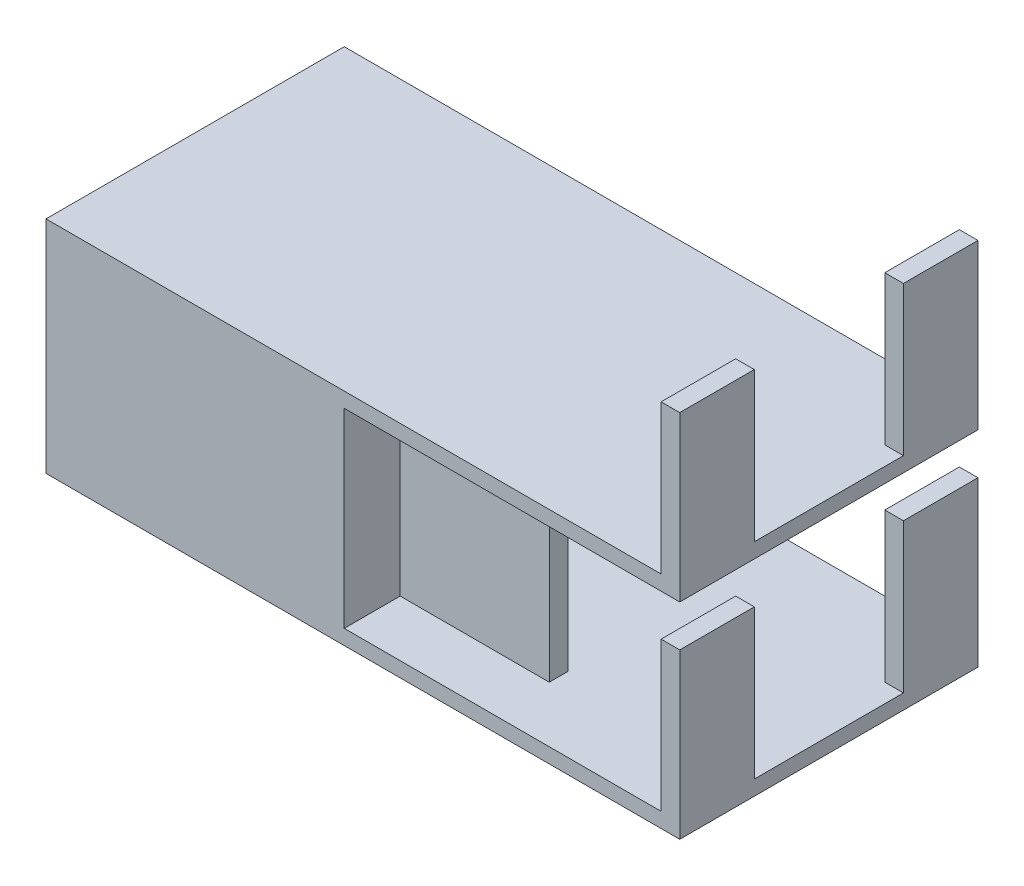
SolidWorks part; units mm, degrees
ref_plane "Front Plane" through (0, 0, 0) normal (0, 0, 1) x (1, 0, 0)
ref_plane "Top Plane" through (0, 0, 0) normal (0, 1, 0) x (1, 0, 0)
ref_plane "Right Plane" through (0, 0, 0) normal (1, 0, 0) x (0, 0, -1)
sketch "Sketch1" plane through (0, 0, 0) normal (0, 1, 0) x (1, 0, 0)
  line L1 (25.4, -25.4) -> (-25.4, -25.4)
  line L2 (25.4, -25.4) -> (25.4, 25.4)
  line L3 (25.4, 25.4) -> (-25.4, 25.4)
  line L4 (-25.4, -25.4) -> (-25.4, 25.4)
  line L5 (25.4, -25.4) -> (-25.4, 25.4) construction
  line L6 (25.4, 25.4) -> (-25.4, -25.4) construction
  point P0 (0, 0)
  dimension "D1" = 50.8
extrude "Boss-Extrude1" add sketch "Sketch1" along normal blind 2.54
sketch "Sketch2" plane through (0, 2.54, 0) normal (0, 1, 0) x (1, 0, 0)
  circle A0 centre (0, 0) radius 19.05
  dimension "D1" = 38.1
extrude "Cut-Extrude1" cut sketch "Sketch2" against normal through all
sketch "Sketch3" plane through (0, 2.54, 0) normal (0, 1, 0) x (1, 0, 0)
  line L1 (15.494, -15.494) -> (-15.494, -15.494) construction
  line L2 (15.494, -15.494) -> (15.494, 15.494) construction
  line L3 (15.494, 15.494) -> (-15.494, 15.494) construction
  line L4 (-15.494, -15.494) -> (-15.494, 15.494) construction
  line L5 (15.494, -15.494) -> (-15.494, 15.494) construction
  line L6 (15.494, 15.494) -> (-15.494, -15.494) construction
  circle A0 centre (-15.494, 15.494) radius 1.905
  circle A1 centre (15.494, 15.494) radius 1.905
  circle A2 centre (15.494, -15.494) radius 1.905
  circle A3 centre (-15.494, -15.494) radius 1.905
  point P0 (0, 0)
  dimension "D2" = 3.81
  dimension "D1" = 30.988
extrude "Cut-Extrude2" cut sketch "Sketch3" against normal through all
sketch "Sketch4" plane through (0, 2.54, 0) normal (0, 1, 0) x (1, 0, 0)
  line L0 (-25.4, -25.4) -> (25.4, -25.4) construction
  line L1 (-10.795, -25.4) -> (10.795, -25.4)
  line L2 (-10.795, -25.4) -> (-10.795, -15.6962)
  line L3 (-10.795, -15.6962) -> (10.795, -15.6962)
  line L4 (10.795, -25.4) -> (10.795, -15.6962)
  circle A0 centre (0, 0) radius 19.05 construction
  point P6 (0, -25.4)
  point P8 (0, 0)
  dimension "D1" = 21.59
extrude "Cut-Extrude3" cut sketch "Sketch4" against normal through all
sketch "Sketch5" plane through (0, 2.54, 0) normal (0, 1, 0) x (1, 0, 0)
  line L1 (-25.4, -25.4) -> (-22.225, -25.4)
  line L2 (-25.4, -25.4) -> (-25.4, -6.35)
  line L3 (-25.4, -6.35) -> (-22.225, -6.35)
  line L4 (-22.225, -25.4) -> (-22.225, -6.35)
  line L5 (25.4, -25.4) -> (22.225, -25.4)
  line L6 (25.4, -25.4) -> (25.4, -6.35)
  line L7 (25.4, -6.35) -> (22.225, -6.35)
  line L8 (22.225, -25.4) -> (22.225, -6.35)
  point P9 (0, 0)
  point P10 (0, 0)
  dimension "D1" = 3.175
  dimension "D2" = 19.05
extrude "Boss-Extrude2" add sketch "Sketch5" along normal blind 35.0058
sketch "Sketch6" plane through (0, 37.5458, 0) normal (0, 1, 0) x (1, 0, 0)
  line L0 (25.4, -25.4) -> (25.4, -6.35) construction
  line L1 (-25.4, -25.4) -> (25.4, -25.4)
  line L2 (-25.4, -25.4) -> (-25.4, 25.4)
  line L4 (25.4, -25.4) -> (25.4, 25.4)
  line L7 (25.4, 25.4) -> (-25.4, 25.4) construction
  line L8 (-25.4, 25.4) -> (25.4, 25.4)
extrude "Boss-Extrude3" add sketch "Sketch6" against normal blind 2.54
sketch "Sketch8" plane through (0, 0, 25.4) normal (0, 0, 1) x (1, 0, 0)
  line L1 (-25.4, 37.5458) -> (25.4, 37.5458)
  line L2 (-25.4, 37.5458) -> (-25.4, 0)
  line L3 (-25.4, 0) -> (25.4, 0)
  line L4 (25.4, 37.5458) -> (25.4, 0)
extrude "Boss-Extrude4" add sketch "Sketch8" against normal blind 2.54
sketch "Sketch9" plane through (0, 35.0058, 0) normal (0, -1, 0) x (1, 0, 0)
  circle A0 centre (0, 0) radius 3.048
  dimension "D1" = 6.096
extrude "Boss-Extrude5" add sketch "Sketch9" along normal blind 5.08
sketch "Sketch10" plane through (0, 0, 0) normal (0, -1, 0) x (1, 0, 0)
  line L0 (25.4, -25.4) -> (-25.4, -25.4) construction
  line L1 (-11.43, -15.24) -> (11.43, -15.24)
  line L2 (-11.43, -15.24) -> (-11.43, -25.4)
  line L3 (-11.43, -25.4) -> (11.43, -25.4)
  line L4 (11.43, -15.24) -> (11.43, -25.4)
  arc A0 (-10.795, 15.6962) -> (10.795, 15.6962) centre (0, 0) ccw construction
  point P7 (0, 0)
  point P10 (0, -15.24)
  point P13 (-8.7719, -25.4)
  dimension "D1" = 22.86
extrude "Cut-Extrude4" cut sketch "Sketch10" against normal up to next
sketch "Sketch13" plane through (25.4, 0, 0) normal (1, 0, 0) x (0, 0, -1)
  line L0 (-6.35, 35.0058) -> (25.4, 35.0058) construction
  line L1 (25.4, 37.5458) -> (-25.4, 37.5458)
  line L2 (25.4, 37.5458) -> (25.4, 35.0058)
  line L3 (25.4, 35.0058) -> (-25.4, 35.0058)
  line L4 (-25.4, 37.5458) -> (-25.4, 35.0058)
  line L5 (-25.4, 37.5458) -> (-25.4, 0) construction
  line L7 (25.4, 2.54) -> (-25.4, 2.54)
  line L8 (25.4, 2.54) -> (25.4, 0)
  line L9 (25.4, 0) -> (-25.4, 0)
  line L10 (-25.4, 2.54) -> (-25.4, 0)
extrude "Boss-Extrude7" add sketch "Sketch13" along normal blind 57.15
sketch "Sketch15" plane through (0, 37.5458, 0) normal (0, 1, 0) x (1, 0, 0)
  line L1 (82.55, 25.4) -> (79.375, 25.4)
  line L2 (82.55, 25.4) -> (82.55, 12.7)
  line L3 (82.55, 12.7) -> (79.375, 12.7)
  line L4 (79.375, 25.4) -> (79.375, 12.7)
  line L5 (82.55, -25.4) -> (79.375, -25.4)
  line L6 (82.55, -25.4) -> (82.55, -12.7)
  line L7 (82.55, -12.7) -> (79.375, -12.7)
  line L8 (79.375, -25.4) -> (79.375, -12.7)
  dimension "D1" = 3.175
  dimension "D2" = 12.7
extrude "Boss-Extrude8" add sketch "Sketch15" along normal blind 25.4
sketch "Sketch17" plane through (0, 2.54, 0) normal (0, 1, 0) x (1, 0, 0)
  line L0 (82.55, -25.4) -> (82.55, -12.7) construction
  line L1 (82.55, -12.7) -> (79.375, -12.7) construction
  line L2 (79.375, -12.7) -> (79.375, -25.4) construction
  line L3 (79.375, -25.4) -> (82.55, -25.4) construction
  line L4 (82.55, 12.7) -> (82.55, 25.4) construction
  line L5 (82.55, 25.4) -> (79.375, 25.4) construction
  line L6 (79.375, 25.4) -> (79.375, 12.7) construction
  line L7 (79.375, 12.7) -> (82.55, 12.7) construction
  line L8 (82.55, -25.4) -> (82.55, -12.7)
  line L9 (82.55, -12.7) -> (79.375, -12.7)
  line L10 (79.375, -12.7) -> (79.375, -25.4)
  line L11 (79.375, -25.4) -> (82.55, -25.4)
  line L12 (82.55, 12.7) -> (82.55, 25.4)
  line L13 (82.55, 25.4) -> (79.375, 25.4)
  line L14 (79.375, 25.4) -> (79.375, 12.7)
  line L15 (79.375, 12.7) -> (82.55, 12.7)
extrude "Boss-Extrude10" add sketch "Sketch17" along normal blind 25.4
sketch "Sketch18" plane through (25.4, 0, 0) normal (1, 0, 0) x (0, 0, -1)
  line L0 (-25.4, 35.0058) -> (25.4, 35.0058) construction
  line L1 (-12.7, 35.0058) -> (-15.875, 35.0058)
  line L2 (-12.7, 35.0058) -> (-12.7, 2.54)
  line L3 (-12.7, 2.54) -> (-15.875, 2.54)
  line L4 (-15.875, 35.0058) -> (-15.875, 2.54)
  line L5 (12.7, 2.54) -> (-12.7, 2.54) construction
  line L6 (-6.35, 35.0058) -> (-6.35, 2.54) construction
  dimension "D1" = 3.175
  dimension "D2" = 6.35
extrude "Boss-Extrude11" add sketch "Sketch18" along normal blind 25.4
